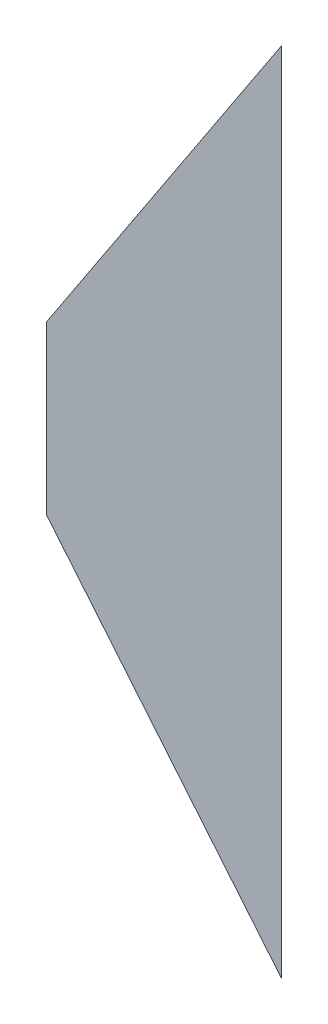
SolidWorks part; units mm, degrees
ref_plane "Plan de face" through (0, 0, 0) normal (0, 0, 1) x (1, 0, 0)
ref_plane "Plan de dessus" through (0, 0, 0) normal (0, 1, 0) x (1, 0, 0)
ref_plane "Plan de droite" through (0, 0, 0) normal (1, 0, 0) x (0, 0, -1)
sketch "Esquisse1" plane through (0, 0, 0) normal (0, 0, 1) x (1, 0, 0)
  line L2 (7, 10.6244) -> (0, 0)
  line L3 (0, 0) -> (0, -5)
  line L5 (0, -5) -> (7, -13.4585)
  line L6 (7, -13.4585) -> (7, 10.6244)
sketch "Esquisse2" plane through (0, 0, 0) normal (1, 0, 0) x (0, 0, -1)
  line L0 (0, 0) -> (0, -5)
  line L1 (0, -5) -> (2.6, -5)
  line L2 (2.6, -5) -> (2.6, 0)
  line L3 (2.6, 0) -> (0, 0)
  dimension "D1" = 2.6
loft "Lissage5" add profiles "Esquisse1", "Esquisse2"
